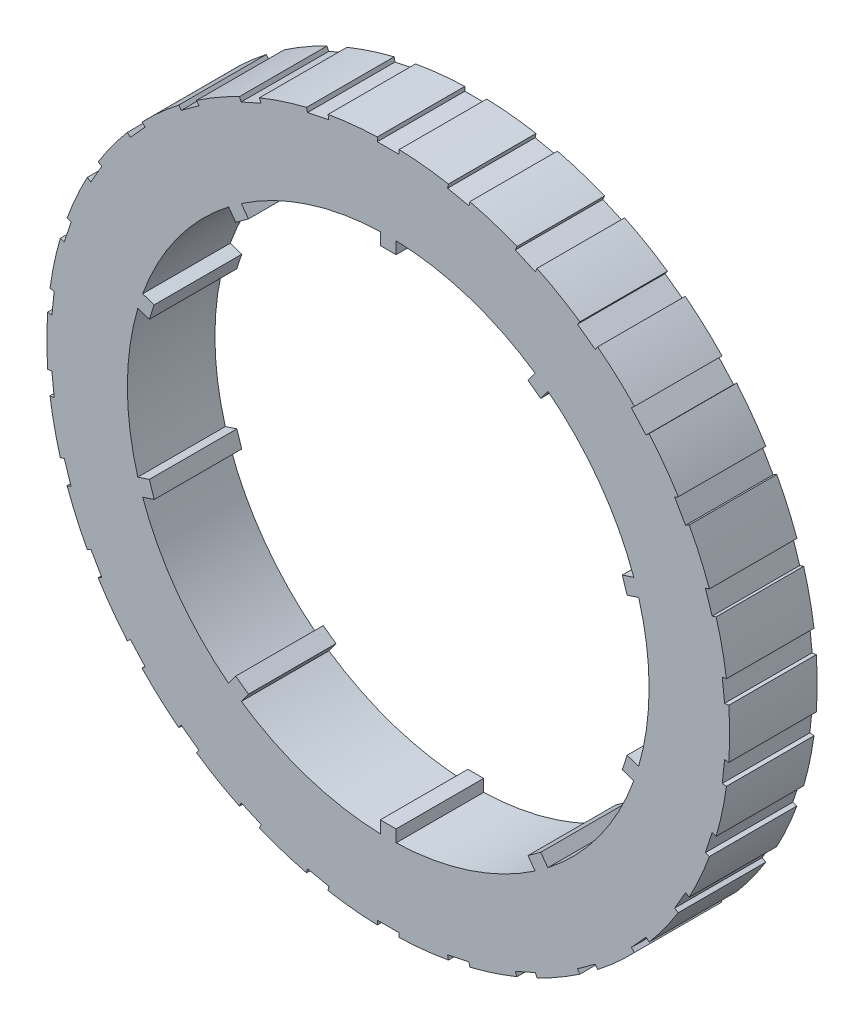
SolidWorks part; units mm, degrees
ref_plane "Front Plane" through (0, 0, 0) normal (0, 0, 1) x (1, 0, 0)
ref_plane "Top Plane" through (0, 0, 0) normal (0, 1, 0) x (1, 0, 0)
ref_plane "Right Plane" through (0, 0, 0) normal (1, 0, 0) x (0, 0, -1)
sketch "Sketch2" plane through (0, 0, 0) normal (0, 0, 1) x (1, 0, 0)
  circle A0 centre (0, 0) radius 39
  dimension "D1" = 78
extrude "Boss-Extrude1" add sketch "Sketch2" along normal blind 10 contours A0
sketch "Sketch3" plane through (0, 0, 0) normal (0, 0, 1) x (1, 0, 0)
  line L0 (0, 0) -> (-29.8, 0) construction
  line L1 (0, 0) -> (0, 29.8) construction
  circle A3 centre (0, 0) radius 29.8
  dimension "D1" = 59.6
extrude "Cut-Extrude1" cut sketch "Sketch3" along normal through all
sketch "Sketch4" plane through (0, 0, 0) normal (0, 0, 1) x (1, 0, 0)
  line L0 (0, 29.8) -> (0, 0) construction
  line L1 (-0.9, 28.4) -> (0.9, 28.4)
  line L2 (-0.9, 28.4) -> (-0.9, 31.2)
  line L3 (-0.9, 31.2) -> (0.9, 31.2)
  line L4 (0.9, 28.4) -> (0.9, 31.2)
  line L5 (-0.9, 28.4) -> (0.9, 31.2) construction
  line L6 (-0.9, 31.2) -> (0.9, 28.4) construction
  circle A0 centre (0, 0) radius 29.8 construction
  point P0 (0, 29.8)
  dimension "D1" = 1.8
  dimension "D2" = 2.8
extrude "Boss-Extrude2" add sketch "Sketch4" along normal up to surface (10 mm away) up to face at (29.8, 0, 10)
pattern_circular "CirPattern1" count 10 over 360 about axis through (0, 0, 0) along (0, 0, 1) of "Boss-Extrude2"
sketch "Sketch5" plane through (0, 0, 0) normal (0, 0, 1) x (1, 0, 0)
  line L0 (0, 39) -> (0, 0) construction
  line L1 (-1.25, 38.5) -> (1.25, 38.5)
  line L2 (-1.25, 38.5) -> (-1.25, 39.5)
  line L3 (-1.25, 39.5) -> (1.25, 39.5)
  line L4 (1.25, 38.5) -> (1.25, 39.5)
  line L5 (-1.25, 38.5) -> (1.25, 39.5) construction
  line L6 (-1.25, 39.5) -> (1.25, 38.5) construction
  circle A0 centre (0, 0) radius 39 construction
  point P0 (0, 39)
  dimension "D1" = 2.5
  dimension "D2" = 1
ref_plane "Plane1" through (0, 0, 5) normal (0, 0, 1) x (1, 0, 0)
extrude "Cut-Extrude2" cut sketch "Sketch5" along normal through all
pattern_circular "CirPattern3" count 30 over 360 about axis through (0, 0, 0) along (0, 0, 1) of "Cut-Extrude2"
